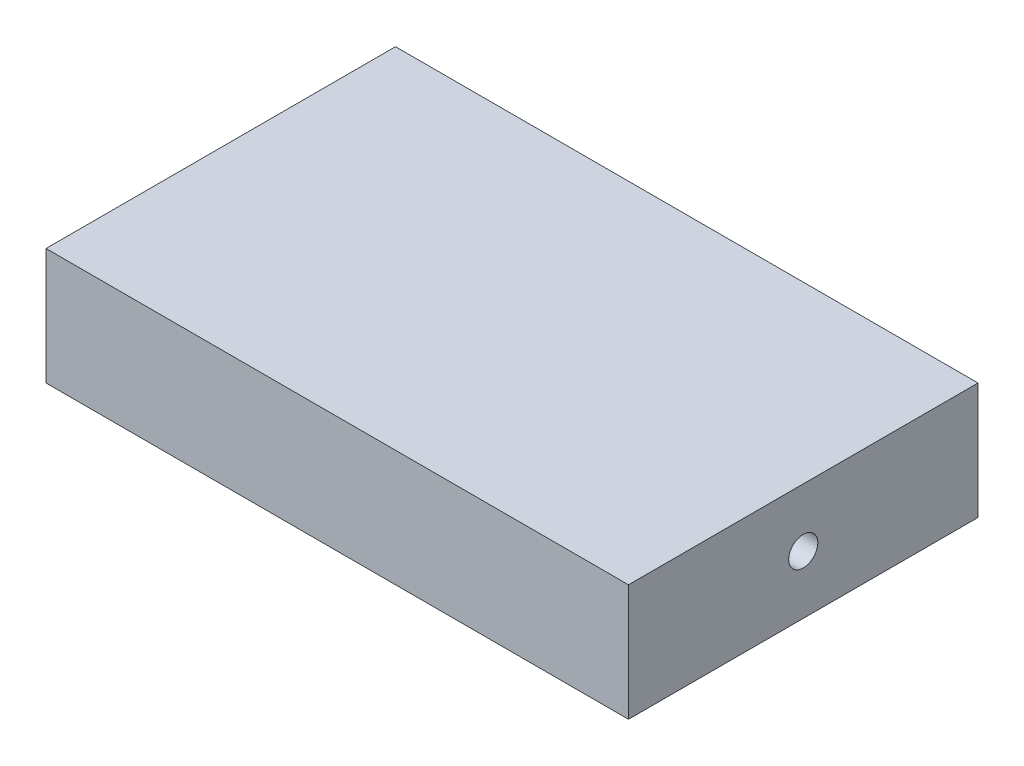
SolidWorks part; units mm, degrees
material "Plain Carbon Steel"
ref_plane "Front Plane" through (0, 0, 0) normal (0, 0, 1) x (1, 0, 0)
ref_plane "Top Plane" through (0, 0, 0) normal (0, 1, 0) x (1, 0, 0)
ref_plane "Right Plane" through (0, 0, 0) normal (1, 0, 0) x (0, 0, -1)
sketch "Sketch1" plane through (0, 0, 0) normal (0, 1, 0) x (1, 0, 0)
  line L1 (-31.75, -19.05) -> (31.75, -19.05)
  line L2 (-31.75, -19.05) -> (-31.75, 19.05)
  line L3 (-31.75, 19.05) -> (31.75, 19.05)
  line L4 (31.75, -19.05) -> (31.75, 19.05)
  line L5 (-31.75, -19.05) -> (31.75, 19.05) construction
  line L6 (-31.75, 19.05) -> (31.75, -19.05) construction
  point P0 (0, 0)
  dimension "D1" = 63.5
  dimension "D2" = 38.1
extrude "Boss-Extrude1" add sketch "Sketch1" along normal blind 12.7
sketch "Sketch2" plane through (0, 12.7, 0) normal (0, 1, 0) x (1, 0, 0)
  line L0 (31.75, -19.05) -> (31.75, 19.05) construction
  line L1 (-31.75, 19.05) -> (31.75, 19.05)
  line L2 (-31.75, 19.05) -> (-31.75, 6.35)
  line L3 (-31.75, 6.35) -> (31.75, 6.35)
  line L4 (31.75, 19.05) -> (31.75, 6.35)
  line L5 (-31.75, 19.05) -> (-31.75, -19.05) construction
  line L6 (31.75, -19.05) -> (-31.75, -19.05)
  line L7 (31.75, -19.05) -> (31.75, -6.35)
  line L8 (31.75, -6.35) -> (-31.75, -6.35)
  line L9 (-31.75, -19.05) -> (-31.75, -6.35)
  dimension "D1" = 12.7
  dimension "D2" = 12.7
extrude "Boss-Extrude2" [suppressed] add sketch "Sketch2" along normal blind 1.016 separate body
sketch "Sketch3" plane through (-31.75, 0, 0) normal (-1, 0, 0) x (0, 0, 1)
  line L0 (-19.05, 12.7) -> (19.05, 0) construction
  line L1 (19.05, 12.7) -> (-19.05, 0) construction
  point P8 (0, 6.35)
hole_wizard "1/8 (0.125) Diameter Hole1" positions "Sketch4" profile "Sketch5" hole size "1/8" standard "ANSI Inch" end condition up to next
sketch "Sketch4" plane through (-31.75, 0, 0) normal (-1, 0, 0) x (0, 0, 1)
  point P0 (0, 6.35)
sketch "Sketch5" plane through (-31.75, 6.35, 0) normal (0, 1, 0) x (0, 0, 1)
  line L0 (0, 0) -> (0, 63.5)
  line L1 (0, 63.5) -> (1.5875, 63.5)
  line L2 (1.5875, 63.5) -> (1.5875, 0)
  line L5 (1.5875, 0) -> (0, 0)
  line L11 (0, -6.35) -> (0, 107.95) construction
  dimension "Thru Hole Dia." = 3.175
  dimension "Thru Hole Depth" = 63.5
